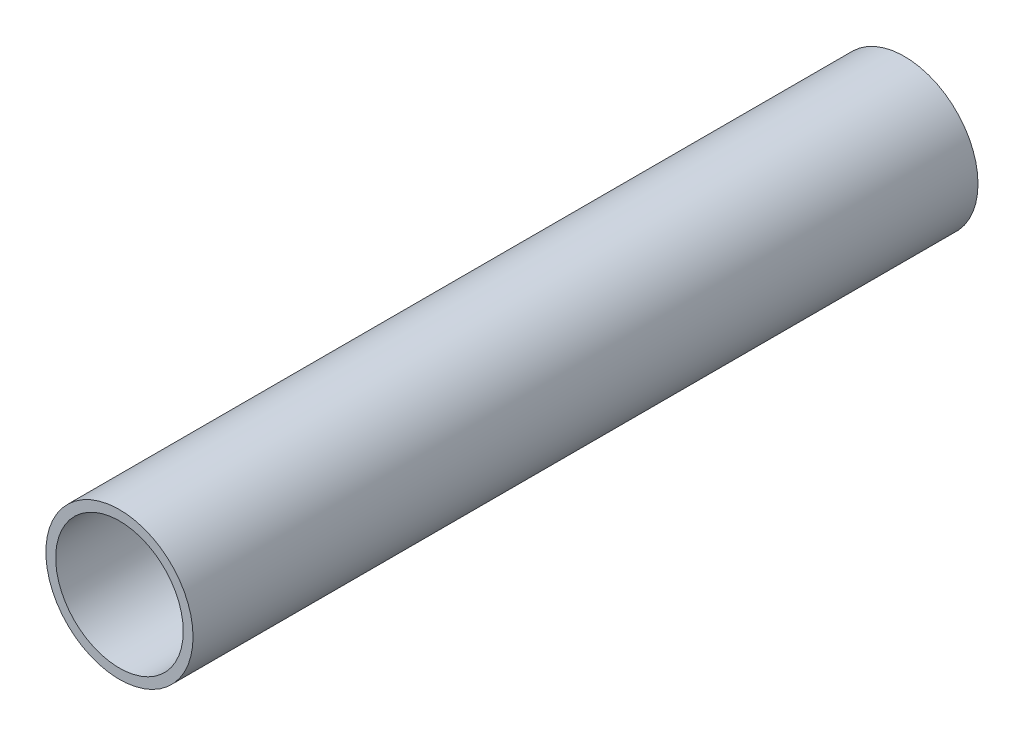
SolidWorks part; units mm, degrees
material "Fibre de verre A"
ref_plane "Plan de face" through (0, 0, 0) normal (0, 0, 1) x (1, 0, 0)
ref_plane "Plan de dessus" through (0, 0, 0) normal (0, 1, 0) x (1, 0, 0)
ref_plane "Plan de droite" through (0, 0, 0) normal (1, 0, 0) x (0, 0, -1)
sketch "Esquisse1" plane through (0, 0, 0) normal (0, 0, 1) x (1, 0, 0)
  circle A0 centre (0, 0) radius 15
  circle A1 centre (0, 0) radius 13
  dimension "D1" = 30
  dimension "D2" = 26
extrude "Boss.-Extru.1" add sketch "Esquisse1" along normal blind 160
